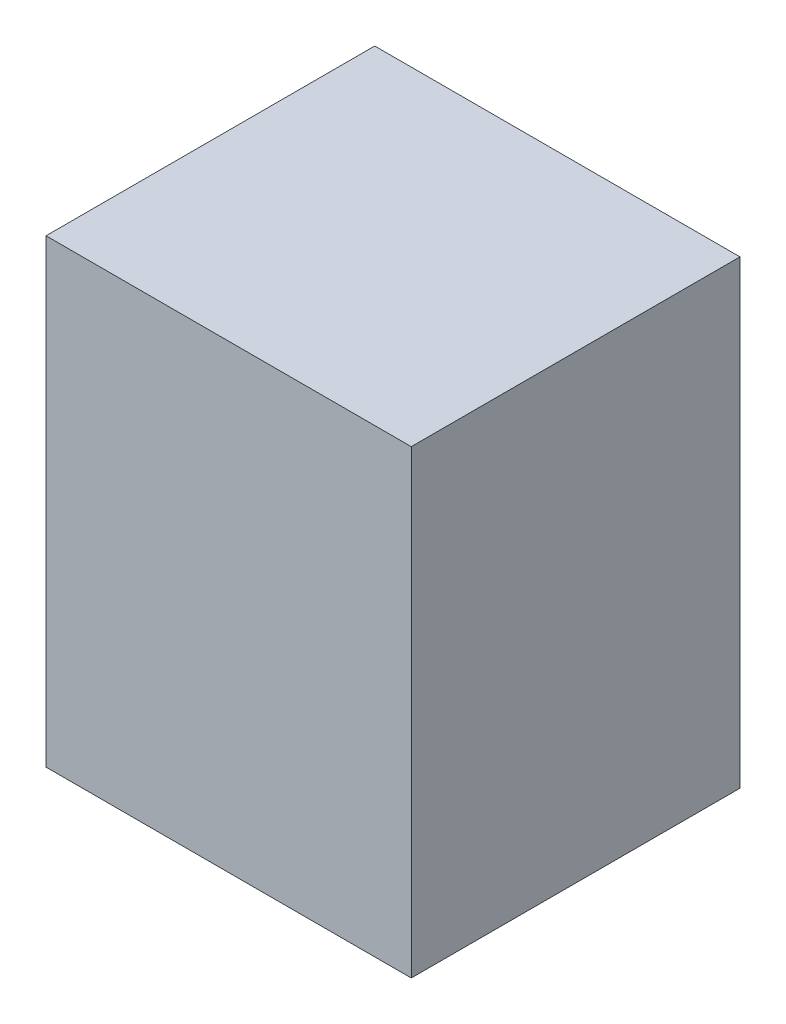
SolidWorks part; units mm, degrees
ref_plane "Front Plane" through (0, 0, 0) normal (0, 0, 1) x (1, 0, 0)
ref_plane "Top Plane" through (0, 0, 0) normal (0, 1, 0) x (1, 0, 0)
ref_plane "Right Plane" through (0, 0, 0) normal (1, 0, 0) x (0, 0, -1)
sketch "Sketch1" plane through (0, 0, 0) normal (0, 0, 1) x (1, 0, 0)
  line L1 (0, 0) -> (10, 0)
  line L2 (0, 0) -> (0, 12.6)
  line L3 (0, 12.6) -> (10, 12.6)
  line L4 (10, 0) -> (10, 12.6)
  dimension "D1" = 12.6
  dimension "D2" = 10
extrude "Boss-Extrude1" add sketch "Sketch1" along normal blind 9
